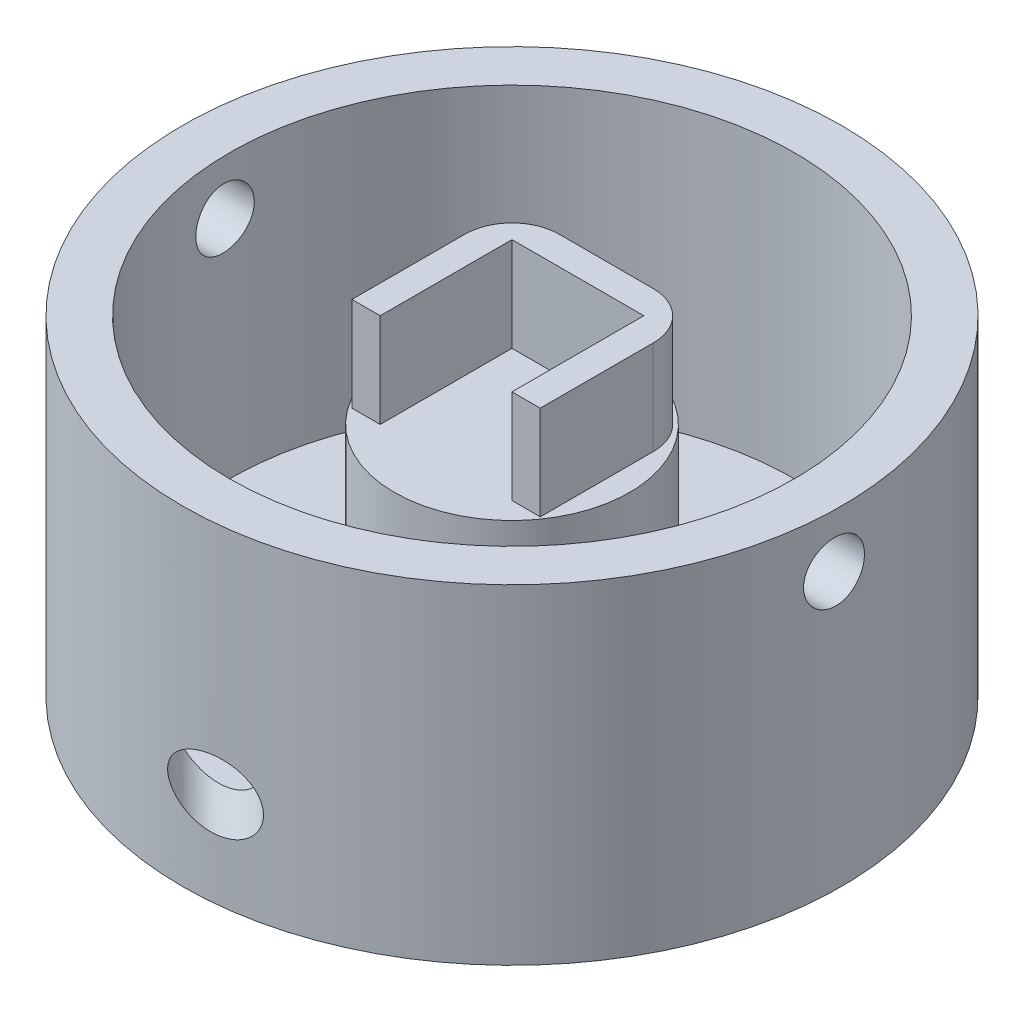
SolidWorks part; units mm, degrees
ref_plane "Front Plane" through (0, 0, 0) normal (0, 0, 1) x (1, 0, 0)
ref_plane "Top Plane" through (0, 0, 0) normal (0, 1, 0) x (1, 0, 0)
ref_plane "Right Plane" through (0, 0, 0) normal (1, 0, 0) x (0, 0, -1)
sketch "Sketch1" plane through (0, 0, 0) normal (0, 1, 0) x (1, 0, 0)
  circle A0 centre (0, 0) radius 35
  dimension "D1" = 70
extrude "Boss-Extrude1" add sketch "Sketch1" along normal blind 35
sketch "Sketch3" plane through (0, 35, 0) normal (0, 1, 0) x (1, 0, 0)
  circle A2 centre (0, 0) radius 30
  circle A3 centre (0, 0) radius 30
  dimension "D1" = 5
extrude "Cut-Extrude1" cut sketch "Sketch3" against normal blind 30
sketch "Sketch4" plane through (0, 5, 0) normal (0, 1, 0) x (1, 0, 0)
  circle A0 centre (0, 0) radius 12.5
extrude "Boss-Extrude2" add sketch "Sketch4" along normal blind 20
ref_plane "Plane1" through (24.7487, 0, 24.7487) normal (0.7071, 0, 0.7071) x (0, -1, 0)
sketch "Sketch5" plane through (24.7487, 0, 24.7487) normal (0.7071, 0, 0.7071) x (0, -1, 0)
  line L0 (0, -35) -> (0, 35) construction
  circle A0 centre (-10, -22.2601) radius 3.6
  dimension "D1" = 7.2
  dimension "D2" = 10
extrude "Cut-Extrude2" cut sketch "Sketch5" against normal blind 20
sketch "Sketch6" plane through (0, 25, 0) normal (0, 1, 0) x (1, 0, 0)
  line L0 (-10, -7) -> (-10, 5)
  line L2 (-7, -7) -> (-7, 7)
  line L3 (-7, 7) -> (7, 7)
  line L4 (7, -7) -> (7, 7)
  line L5 (-7, -7) -> (7, 7) construction
  line L6 (-7, 7) -> (7, -7) construction
  line L7 (-5, 10) -> (5, 10)
  line L8 (10, -7) -> (10, 5)
  line L10 (7, -7) -> (10, -7)
  line L11 (-7, -7) -> (-10, -7)
  line L12 (-10, 10) -> (10, 10) construction
  line L13 (-10, -10) -> (10, -10) construction
  line L14 (-10, -10) -> (-10, 10) construction
  line L15 (10, -10) -> (10, 10) construction
  line L16 (-7, -7) -> (7, -7) construction
  arc A0 (-10, 5) -> (-5, 10) centre (-5, 5) cw
  arc A1 (5, 10) -> (10, 5) centre (5, 5) cw
  point P0 (0, 0)
  dimension "D3" = 5
  dimension "D1" = 14
  dimension "D2" = 3
extrude "Boss-Extrude3" add sketch "Sketch6" along normal blind 10
sketch "Sketch8" plane through (10, 0, 0) normal (1, 0, 0) x (0, 0, -1)
  line L0 (-7, 35) -> (-7, 25) construction
  line L1 (-7, 35) -> (5, 35) construction
  circle A0 centre (-0.65, 29.285) radius 3.175
  dimension "D1" = 6.35
  dimension "D2" = 6.35
  dimension "D3" = 5.715
extrude "Cut-Extrude4" cut sketch "Sketch8" along normal through all
sketch "Sketch10" plane through (-10, 0, 0) normal (-1, 0, 0) x (0, 0, 1)
  line L0 (-5, 35) -> (7, 35) construction
  line L1 (7, 35) -> (7, 25) construction
  circle A0 centre (0.65, 29.285) radius 3.175
  dimension "D1" = 6.35
  dimension "D2" = 5.715
  dimension "D3" = 6.35
extrude "Cut-Extrude5" cut sketch "Sketch10" along normal through all
